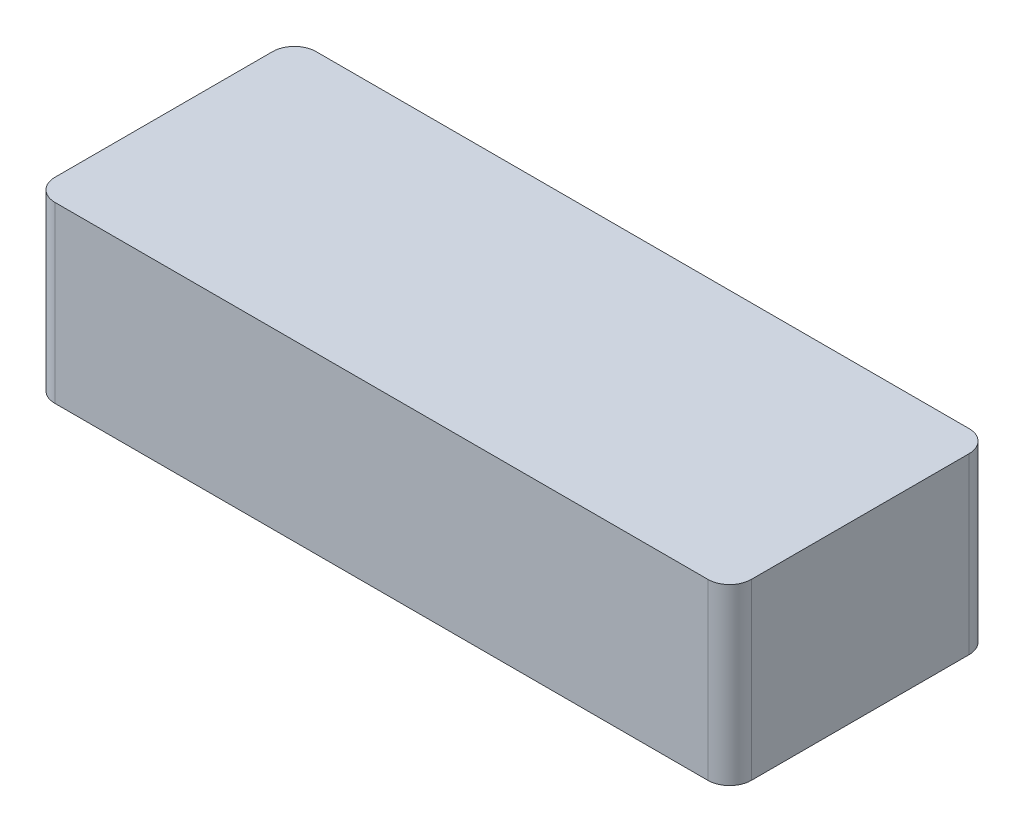
SolidWorks part; units mm, degrees
ref_plane "Front Plane" through (0, 0, 0) normal (0, 0, 1) x (1, 0, 0)
ref_plane "Top Plane" through (0, 0, 0) normal (0, 1, 0) x (1, 0, 0)
ref_plane "Right Plane" through (0, 0, 0) normal (1, 0, 0) x (0, 0, -1)
sketch "Sketch1" plane through (0, 0, 0) normal (0, 1, 0) x (1, 0, 0)
  line L1 (-80, -30) -> (80, -30)
  line L2 (-80, -30) -> (-80, 30)
  line L3 (-80, 30) -> (80, 30)
  line L4 (80, -30) -> (80, 30)
  line L5 (-80, -30) -> (80, 30) construction
  line L6 (-80, 30) -> (80, -30) construction
  point P0 (0, 0)
  dimension "D1" = 160
  dimension "D2" = 60
extrude "Boss-Extrude1" add sketch "Sketch1" along normal blind 40
fillet "Fillet1" radius 5 4 edges at (80, 20, 30) (80, 20, -30) (-80, 20, 30) (-80, 20, -30)
